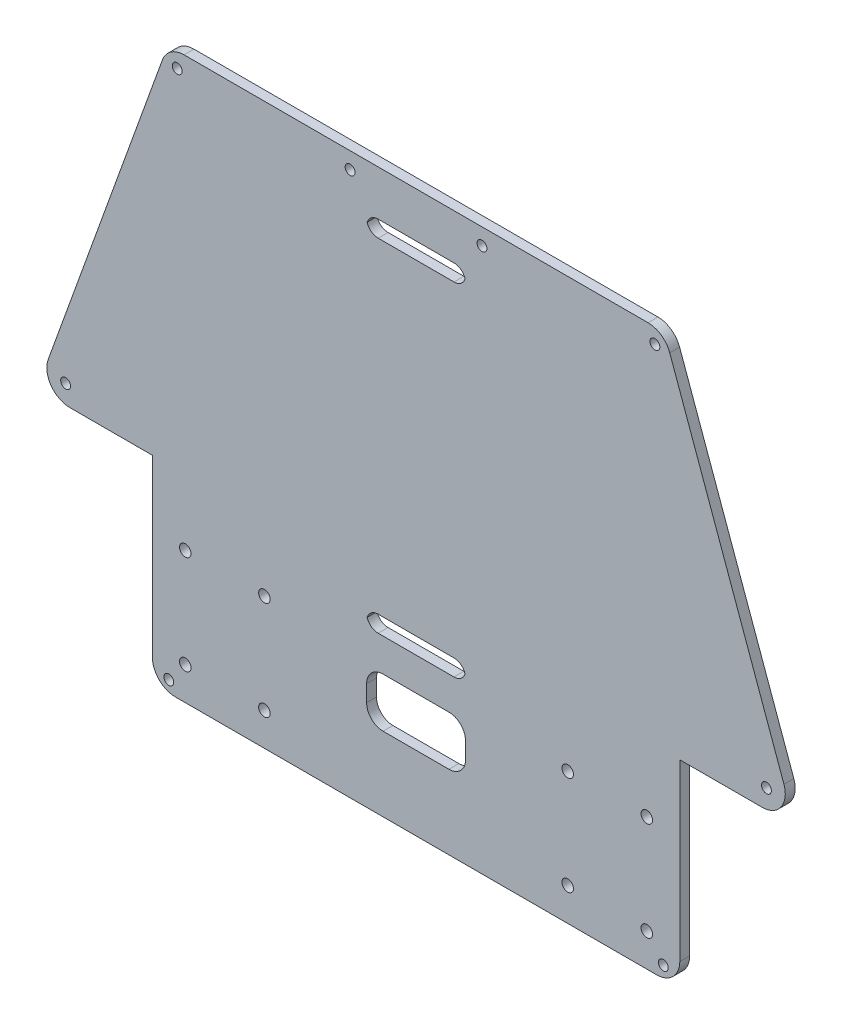
SolidWorks part; units mm, degrees
ref_plane "前视基准面" through (0, 0, 0) normal (0, 0, 1) x (1, 0, 0)
ref_plane "上视基准面" through (0, 0, 0) normal (0, 1, 0) x (1, 0, 0)
ref_plane "右视基准面" through (0, 0, 0) normal (1, 0, 0) x (0, 0, -1)
sketch "草图2" plane through (0, 0, 0) normal (0, 0, 1) x (1, 0, 0)
  line L0 (0, 170) -> (0, 0) construction
  line L1 (-73, 0) -> (73, 0)
  line L2 (-58, 40.7094) -> (-58, 5.5717) construction
  line L3 (-70.3629, 170) -> (70.3629, 170)
  line L4 (58, 40.7094) -> (58, 5.5717) construction
  line L5 (-11.4906, 151.2779) -> (11.5094, 151.2779)
  line L6 (-11.5, 47.5) -> (11.5, 47.5)
  line L7 (-80, 7) -> (-80, 60)
  line L8 (-80, 60) -> (-105, 60)
  line L9 (-111.5845, 69.3757) -> (-76.9474, 165.3757)
  line L10 (80, 7) -> (80, 60)
  line L11 (80, 60) -> (105, 60)
  line L12 (111.5845, 69.3757) -> (76.9474, 165.3757)
  line L14 (-11.5, 52.5) -> (11.5, 52.5)
  line L16 (-12.9931, 47.8345) -> (12.9931, 52.1655) construction
  line L17 (-12.9931, 52.1655) -> (12.9931, 47.8345) construction
  line L19 (-11.4906, 156.2779) -> (11.5094, 156.2779)
  line L21 (-14.9906, 151.2779) -> (15.0094, 156.2779) construction
  line L22 (-14.9906, 156.2779) -> (15.0094, 151.2779) construction
  line L23 (-10, 22.5) -> (10, 22.5)
  line L24 (-15, 27.5) -> (-15, 32.5)
  line L25 (-10, 37.5) -> (10, 37.5)
  line L26 (15, 27.5) -> (15, 32.5)
  line L27 (-15, 22.5) -> (15, 37.5) construction
  line L28 (-15, 37.5) -> (15, 22.5) construction
  arc A0 (105, 60) -> (111.5845, 69.3757) centre (105, 67) ccw
  arc A1 (73, 0) -> (80, 7) centre (73, 7) ccw
  arc A2 (-105, 60) -> (-111.5845, 69.3757) centre (-105, 67) cw
  arc A3 (-80, 7) -> (-73, 0) centre (-73, 7) ccw
  arc A4 (-76.9474, 165.3757) -> (-70.3629, 170) centre (-70.3629, 163) cw
  arc A5 (76.9474, 165.3757) -> (70.3629, 170) centre (70.3629, 163) ccw
  circle A6 centre (-70, 10) radius 1.75
  circle A7 centre (-70, 40) radius 1.75
  circle A8 centre (-46, 40) radius 1.75
  circle A9 centre (-46, 10) radius 1.75
  circle A10 centre (46, 10) radius 1.75
  circle A11 centre (46, 40) radius 1.75
  circle A12 centre (70, 40) radius 1.75
  circle A13 centre (70, 10) radius 1.75
  circle A14 centre (-72.4414, 165.3757) radius 1.5
  circle A15 centre (-106.2915, 65.7561) radius 1.5
  circle A16 centre (106.2915, 65.7561) radius 1.5
  circle A17 centre (72.4414, 165.3757) radius 1.5
  arc A18 (10, 22.5) -> (15, 27.5) centre (10, 27.5) ccw
  arc A19 (-15, 32.5) -> (-10, 37.5) centre (-10, 32.5) cw
  arc A20 (-10, 22.5) -> (-15, 27.5) centre (-10, 27.5) cw
  arc A21 (10, 37.5) -> (15, 32.5) centre (10, 32.5) cw
  circle A22 centre (-20, 165) radius 1.5
  circle A23 centre (20, 165) radius 1.5
  circle A24 centre (-75, 3.552) radius 1.5
  circle A25 centre (75, 3.552) radius 1.5
  arc A26 (-14.8541, 50) -> (-11.5, 52.5) centre (-11.5, 49) cw
  arc A27 (-11.5, 47.5) -> (-14.8541, 50) centre (-11.5, 51) cw
  arc A28 (11.5, 47.5) -> (14.8541, 50) centre (11.5, 51) ccw
  arc A29 (11.5, 52.5) -> (14.8541, 50) centre (11.5, 49) cw
  arc A30 (-14.8447, 153.7779) -> (-11.4906, 156.2779) centre (-11.4906, 152.7779) cw
  arc A31 (-11.4906, 151.2779) -> (-14.8447, 153.7779) centre (-11.4906, 154.7779) cw
  arc A32 (11.5094, 151.2779) -> (14.8635, 153.7779) centre (11.5094, 154.7779) ccw
  arc A33 (11.5094, 156.2779) -> (14.8635, 153.7779) centre (11.5094, 152.7779) cw
  point P0 (0, 0)
  point P49 (0, 30)
  point P74 (0, 50)
  point P98 (0.0094, 153.7779)
  dimension "D1" = 170
  dimension "D6" = 30
  dimension "D7" = 5
  dimension "D10" = 5
  dimension "D11" = 3
  dimension "D12" = 3
  dimension "D13" = 7
  dimension "D2" = 3.5
  dimension "D8" = 3
  dimension "D14" = 7
  dimension "D15" = 24
  dimension "D3" = 3.5
  dimension "D16" = 30
  dimension "D17" = 10
  dimension "D18" = 3
  dimension "D19" = 10
  dimension "D24" = 20
  dimension "D26" = 3.5
  dimension "D28" = 3.5
  dimension "D29" = 5
  dimension "D4" = 15
  dimension "D5" = 30
  dimension "D9" = 40
  dimension "D20" = 160
  dimension "D21" = 150
  dimension "D22" = 25
  dimension "D23" = 25
extrude "凸台-拉伸2" add sketch "草图2" along normal blind 3
